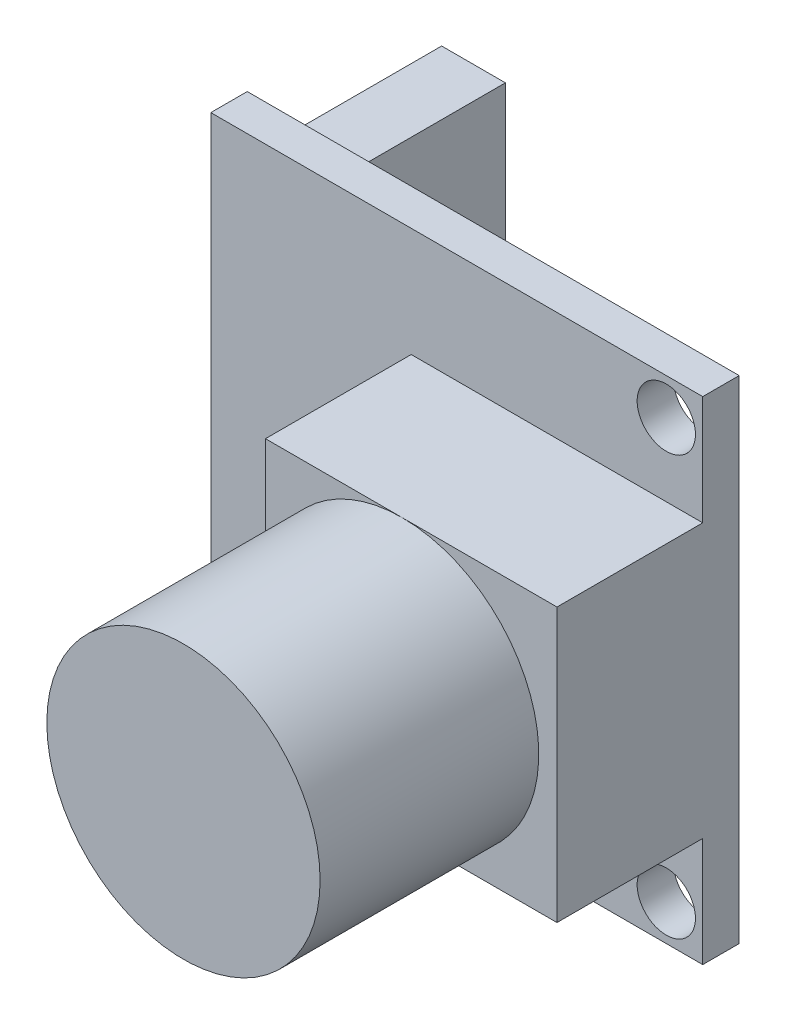
SolidWorks part; units mm, degrees
ref_plane "前视基准面" through (0, 0, 0) normal (0, 0, 1) x (1, 0, 0)
ref_plane "上视基准面" through (0, 0, 0) normal (0, 1, 0) x (1, 0, 0)
ref_plane "右视基准面" through (0, 0, 0) normal (1, 0, 0) x (0, 0, -1)
sketch "草图1" plane through (0, 0, 0) normal (0, 0, 1) x (1, 0, 0)
  line L1 (268.5, 333.5) -> (241.5, 333.5)
  line L2 (268.5, 333.5) -> (268.5, 306.5)
  line L3 (268.5, 306.5) -> (241.5, 306.5)
  line L4 (241.5, 333.5) -> (241.5, 306.5)
  circle A1 centre (266.5, 331.5) radius 1.6
  circle A2 centre (266.5, 308.5) radius 1.6
  dimension "D1" = 27
  dimension "D4" = 27
extrude "凸台-拉伸1" add sketch "草图1" along normal blind 2
sketch "草图2" plane through (0, 0, 2) normal (0, 0, 1) x (1, 0, 0)
  circle A0 centre (260, 320) radius 7.5
  dimension "D1" = 15
extrude "凸台-拉伸2" add sketch "草图2" along normal blind 20
sketch "草图3" plane through (0, 0, 2) normal (0, 0, 1) x (1, 0, 0)
  line L0 (268.5, 306.5) -> (268.5, 333.5) construction
  line L1 (268.5, 327.5) -> (252.5, 327.5)
  line L2 (268.5, 327.5) -> (268.5, 312.5)
  line L3 (268.5, 312.5) -> (252.5, 312.5)
  line L4 (252.5, 327.5) -> (252.5, 312.5)
  circle A0 centre (260, 320) radius 7.5 construction
  dimension "D1" = 7.5
  dimension "D2" = 7.5
  dimension "D3" = 15
extrude "凸台-拉伸3" add sketch "草图3" along normal blind 8
sketch "草图4" plane through (0, 0, 0) normal (0, 0, -1) x (-1, 0, 0)
  line L0 (-241.5, 306.5) -> (-268.5, 306.5) construction
  line L1 (-242.17, 309) -> (-245.67, 309)
  line L2 (-242.17, 309) -> (-242.17, 331)
  line L3 (-242.17, 331) -> (-245.67, 331)
  line L4 (-245.67, 309) -> (-245.67, 331)
  line L5 (-241.5, 333.5) -> (-241.5, 306.5) construction
  dimension "D1" = 22
  dimension "D2" = 2.5
  dimension "D3" = 0.67
  dimension "D4" = 3.5
extrude "凸台-拉伸4" add sketch "草图4" along normal blind 10
